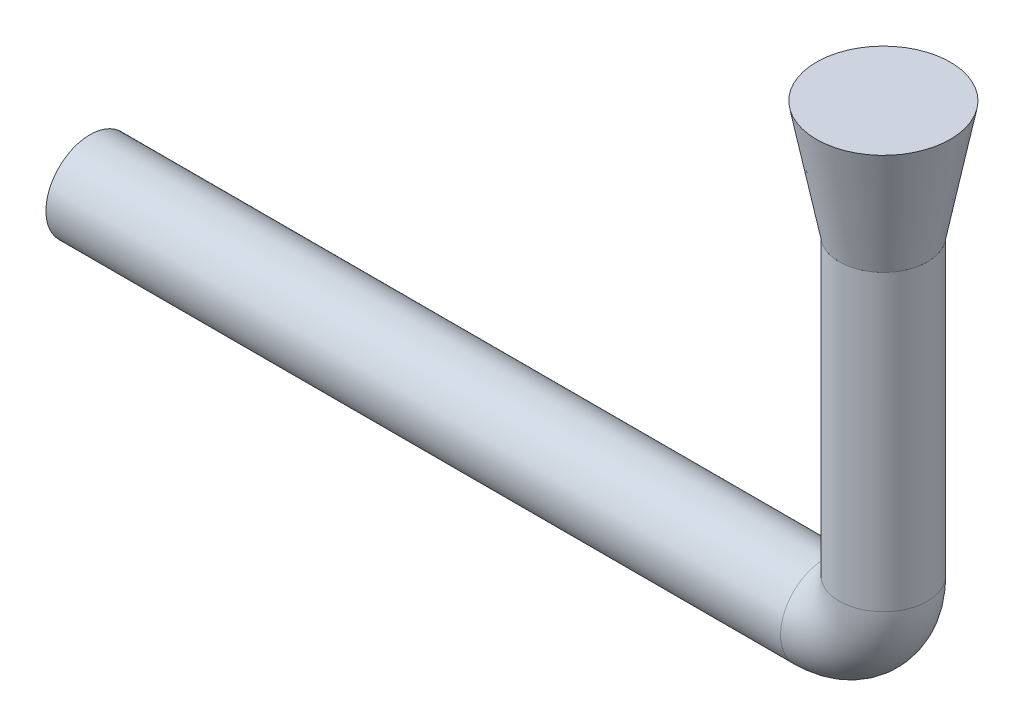
SolidWorks part; units mm, degrees
ref_plane "Front Plane" through (0, 0, 0) normal (0, 0, 1) x (1, 0, 0)
ref_plane "Top Plane" through (0, 0, 0) normal (0, 1, 0) x (1, 0, 0)
ref_plane "Right Plane" through (0, 0, 0) normal (1, 0, 0) x (0, 0, -1)
sketch "Sketch1" plane through (0, 0, 0) normal (0, 0, 1) x (1, 0, 0)
  line L0 (0, 0) -> (250, 0)
  line L1 (270, 20) -> (270, 120)
  arc A0 (250, 0) -> (270, 20) centre (250, 20) ccw
  dimension "D1" = 20
  dimension "D2" = 250
  dimension "D3" = 100
sweep "Sweep1" add path "Sketch1" circular profile diameter 30 parameters "D3"=30
sketch "Sketch30" plane through (0, 120, 0) normal (0, 1, 0) x (1, 0, 0)
  circle A1 centre (270, 0) radius 15
  circle A2 centre (270, 0) radius 15
  dimension "D1" = 0
extrude "Boss-Extrude1" add sketch "Sketch30" along normal blind 40 draft 11 separate body draft outward yes
